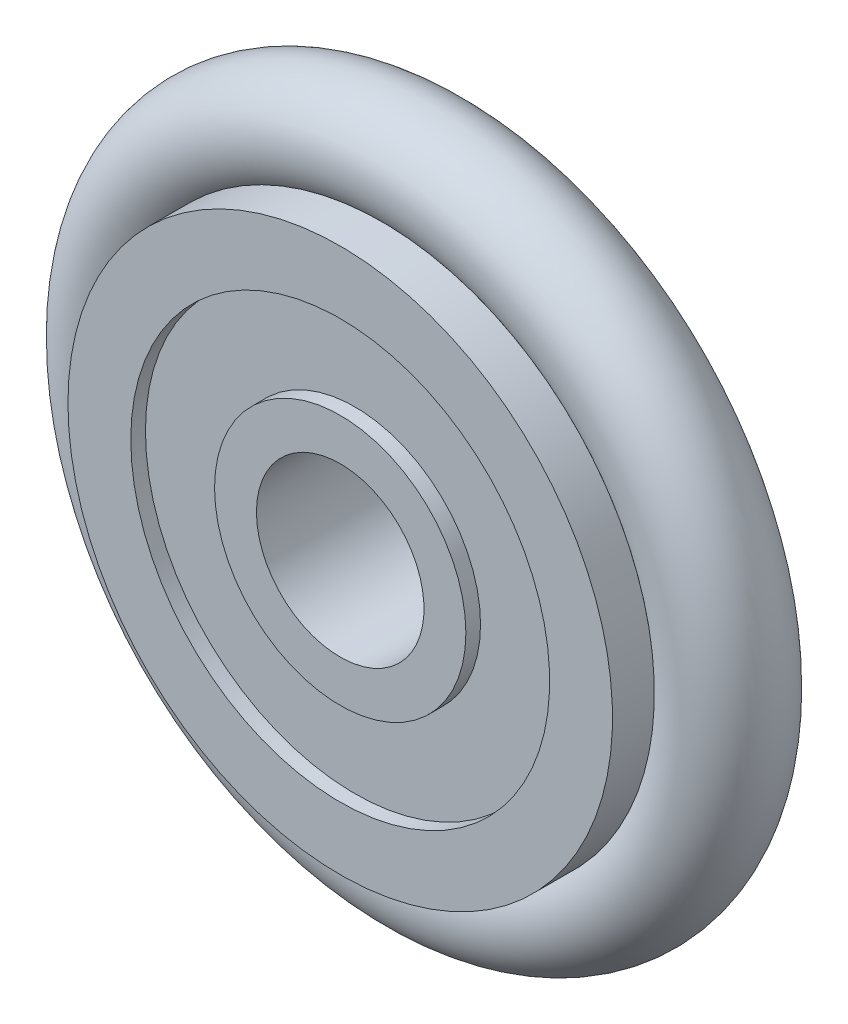
SolidWorks part; units mm, degrees
other "O-Ring"
other "Bearing Center"
ref_plane "Top" through (0, 0, 0) normal (0, 0, 1) x (1, 0, 0)
ref_plane "Front" through (0, 0, 0) normal (0, 1, 0) x (1, 0, 0)
ref_plane "Right" through (0, 0, 0) normal (1, 0, 0) x (0, 0, -1)
sketch "Sketch1" plane through (0, 0, 0) normal (0, 1, 0) x (1, 0, 0)
  line L0 (2, 2) -> (2, -2)
  line L1 (2, -2) -> (3, -2)
  line L2 (3, -2) -> (3, -1.65)
  line L3 (3, -1.65) -> (5, -1.65)
  line L4 (5, -1.65) -> (5, -2)
  line L5 (5, -2) -> (6.5, -2)
  line L6 (6.5, -2) -> (6.5, -1)
  line L7 (0, 2) -> (0, -2) construction
  line L8 (0, 2) -> (2, 2) construction
  line L9 (0, -2) -> (2, -2) construction
  line L10 (0, 0) -> (2, 0) construction
  line L11 (6.5, 2) -> (6.5, 1)
  line L12 (5, 2) -> (6.5, 2)
  line L13 (5, 1.65) -> (5, 2)
  line L14 (3, 1.65) -> (5, 1.65)
  line L15 (3, 2) -> (3, 1.65)
  line L16 (2, 2) -> (3, 2)
  arc A0 (6.5, -1) -> (6.5, 1) centre (7.25, 0) cw
  point P11 (0, 0)
  dimension "D8" = 1.25
  dimension "D1" = 4
  dimension "D2" = 1
  dimension "D3" = 2
  dimension "D4" = 6.5
  dimension "D5" = 2
  dimension "D6" = 1
  dimension "D7" = 0.35
revolve "Revolve1" add sketch "Sketch1" angle 360 about L7
sketch "Sketch6" plane through (0, 0, 0) normal (0, 1, 0) x (1, 0, 0)
  line L0 (0, 0) -> (0, 5) construction
  circle A0 centre (7.25, 0) radius 1.25
  dimension "D1" = 2.5
  dimension "D2" = 7.25
  dimension "D3" = 5
revolve "O-Ring Revolve" add sketch "Sketch6" angle 360 about L0
